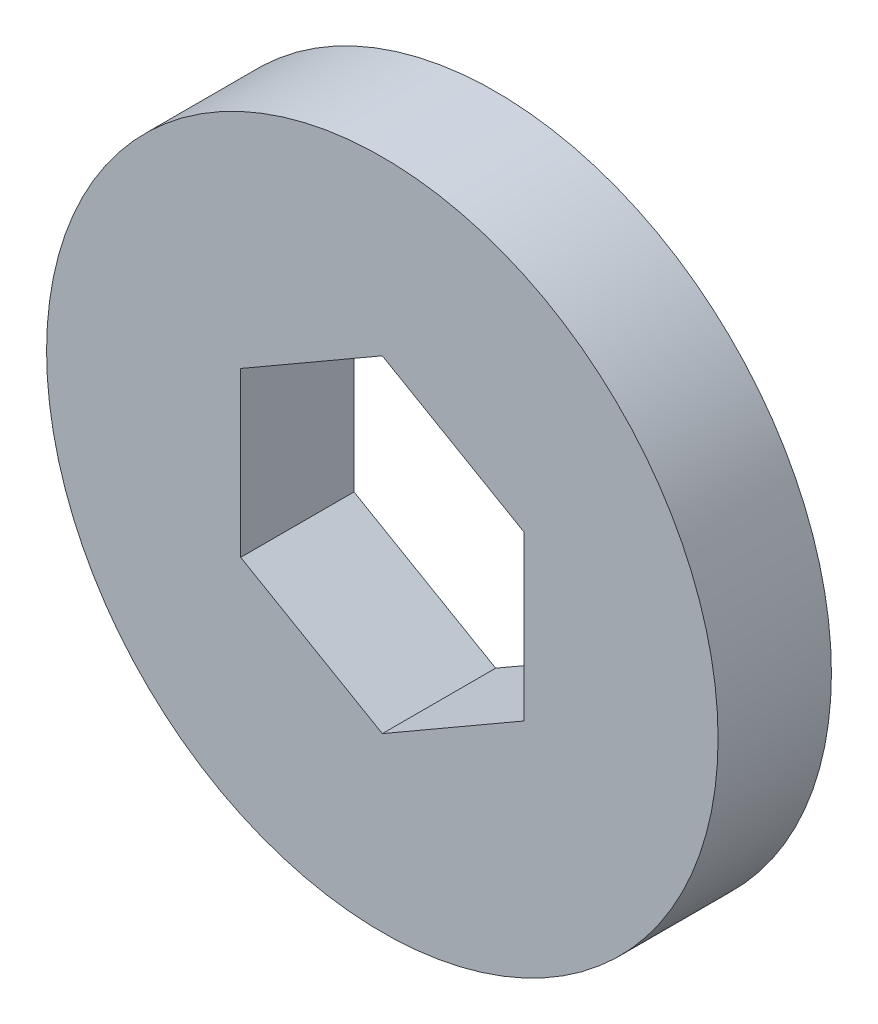
SolidWorks part; units mm, degrees
ref_plane "Front Plane" through (0, 0, 0) normal (0, 0, 1) x (1, 0, 0)
ref_plane "Top Plane" through (0, 0, 0) normal (0, 1, 0) x (1, 0, 0)
ref_plane "Right Plane" through (0, 0, 0) normal (1, 0, 0) x (0, 0, -1)
sketch "Sketch1" plane through (0, 0, 0) normal (0, 0, 1) x (1, 0, 0)
  circle A0 centre (0, 0) radius 11.85
  dimension "D1" = 23.7
extrude "Boss-Extrude1" add sketch "Sketch1" along normal blind 4
sketch "Sketch2" plane through (0, 0, 0) normal (0, 0, -1) x (-1, 0, 0)
  line L1 (0, 5.7735) -> (-5, 2.8868)
  line L2 (-5, 2.8868) -> (-5, -2.8868)
  line L3 (-5, -2.8868) -> (0, -5.7735)
  line L4 (0, -5.7735) -> (5, -2.8868)
  line L5 (5, -2.8868) -> (5, 2.8868)
  line L6 (5, 2.8868) -> (0, 5.7735)
  circle A0 centre (0, 0) radius 5 construction
  dimension "D1" = 10
extrude "Cut-Extrude1" cut sketch "Sketch2" against normal through all
scale "Scale1" scale about centroid uniform scaling yes scale factor 0.4
